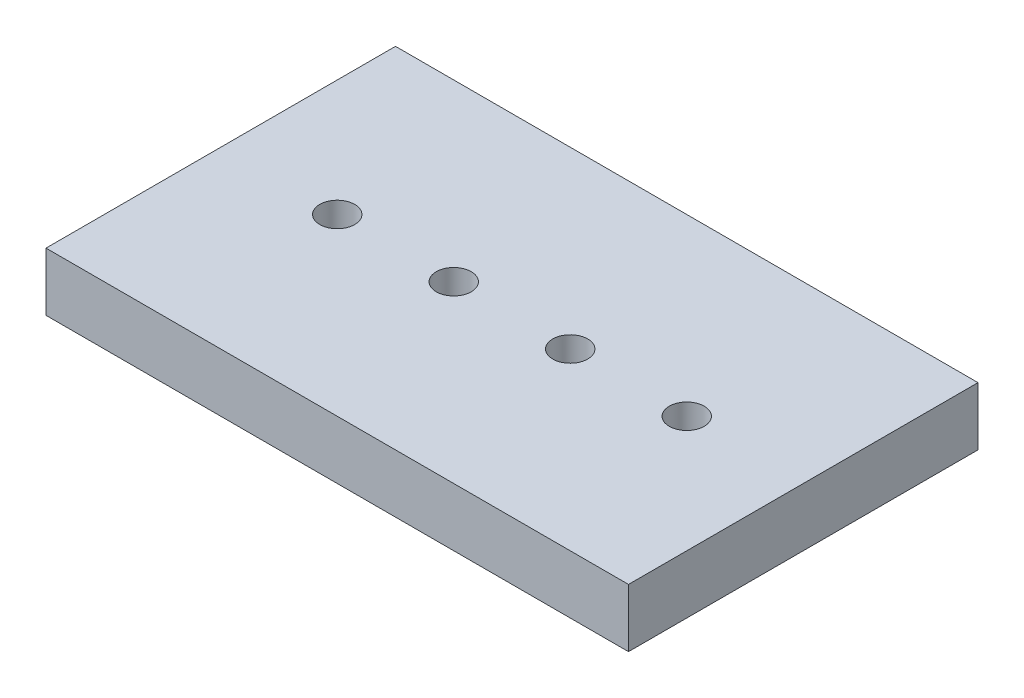
SolidWorks part; units mm, degrees
ref_plane "前视基准面" through (0, 0, 0) normal (0, 0, 1) x (1, 0, 0)
ref_plane "上视基准面" through (0, 0, 0) normal (0, 1, 0) x (1, 0, 0)
ref_plane "右视基准面" through (0, 0, 0) normal (1, 0, 0) x (0, 0, -1)
other "Configuration Table"
sketch "草图1" plane through (0, 0, 0) normal (0, 1, 0) x (1, 0, 0)
  line L1 (-50, -30) -> (50, -30)
  line L2 (-50, -30) -> (-50, 30)
  line L3 (-50, 30) -> (50, 30)
  line L4 (50, -30) -> (50, 30)
  line L5 (0, 30) -> (0, -30) construction
  line L6 (-50, 0) -> (50, 0) construction
  point P0 (0, 0)
extrude "凸台-拉伸1" add sketch "草图1" along normal blind 10
sketch "草图2" plane through (0, 0, 0) normal (0, 1, 0) x (1, 0, 0)
  circle A0 centre (-30, 0) radius 3
extrude "切除-拉伸1" cut sketch "草图2" along normal blind 20
pattern_linear "阵列(线性)1" count 4 spacing 20 along (1, 0, 0) of "切除-拉伸1"
